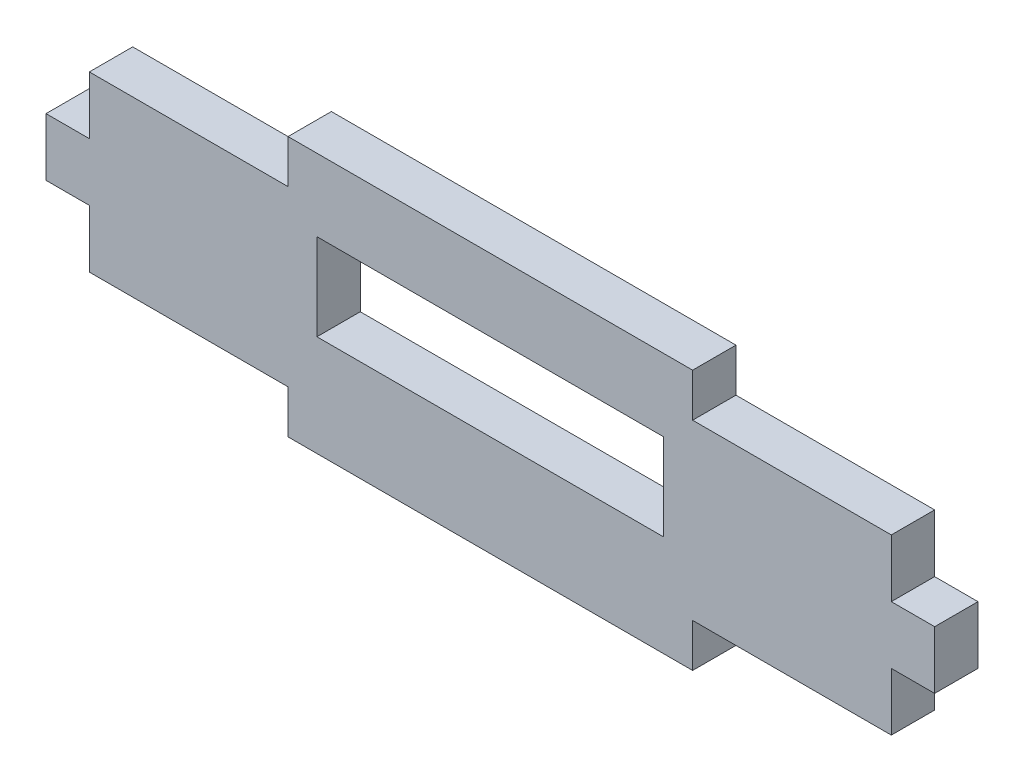
SolidWorks part; units mm, degrees
ref_plane "Front Plane" through (0, 0, 0) normal (0, 0, 1) x (1, 0, 0)
ref_plane "Top Plane" through (0, 0, 0) normal (0, 1, 0) x (1, 0, 0)
ref_plane "Right Plane" through (0, 0, 0) normal (1, 0, 0) x (0, 0, -1)
sketch "Sketch1" plane through (0, 0, 0) normal (0, 0, 1) x (1, 0, 0)
  line L1 (-30.75, -9) -> (30.75, -9) construction
  line L2 (-30.75, -9) -> (-30.75, 9) construction
  line L3 (-30.75, 9) -> (30.75, 9) construction
  line L4 (30.75, -9) -> (30.75, 9) construction
  line L5 (-30.75, -9) -> (30.75, 9) construction
  line L6 (-30.75, 9) -> (30.75, -9) construction
  line L11 (-44.5985, -13.0532) -> (45.3444, 13.2715) construction
  line L12 (-46.4777, 5.9587) -> (46.4777, -5.9587) construction
  line L14 (-14, -9) -> (14, -9)
  line L19 (30.75, -2) -> (30.75, 2)
  line L24 (14, 9) -> (-14, 9)
  line L29 (-30.75, 2) -> (-30.75, -2)
  line L32 (-14, -9) -> (-14, -6)
  line L33 (-14, -6) -> (-30.75, -6) construction
  line L34 (-14, 9) -> (-14, 6)
  line L35 (-14, 6) -> (-30.75, 6) construction
  line L38 (14, 9) -> (14, 6)
  line L39 (14, 6) -> (30.75, 6) construction
  line L42 (30.75, -6) -> (14, -6) construction
  line L43 (14, -6) -> (14, -9)
  line L44 (30.75, 2) -> (27.75, 2)
  line L45 (27.75, 2) -> (27.75, 6)
  line L46 (30.75, -2) -> (27.75, -2)
  line L47 (27.75, -2) -> (27.75, -6)
  line L48 (-30.75, 2) -> (-27.75, 2)
  line L49 (-27.75, 2) -> (-27.75, 6)
  line L50 (-30.75, -2) -> (-27.75, -2)
  line L51 (-27.75, -2) -> (-27.75, -6)
  line L52 (14, 6) -> (27.75, 6)
  line L53 (27.75, -6) -> (14, -6)
  line L54 (-27.75, 6) -> (-14, 6)
  line L55 (-14, -6) -> (-27.75, -6)
  line L57 (-12, -2) -> (12, -2)
  line L58 (-12, -2) -> (-12, 4)
  line L59 (-12, 4) -> (12, 4)
  line L60 (12, -2) -> (12, 4)
  line L61 (-12, -2) -> (12, 4) construction
  line L62 (-12, 4) -> (12, -2) construction
  point P0 (0, 0)
  point P6 (0, 0)
  point P35 (0, 0)
  point P42 (0, 1)
  dimension "D1" = 61.5
  dimension "D2" = 18
  dimension "D3" = 3
  dimension "D4" = 24
  dimension "D5" = 6
  dimension "D6" = 1
  dimension "D7" = 28
extrude "Boss-Extrude1" add sketch "Sketch1" along normal blind 3
